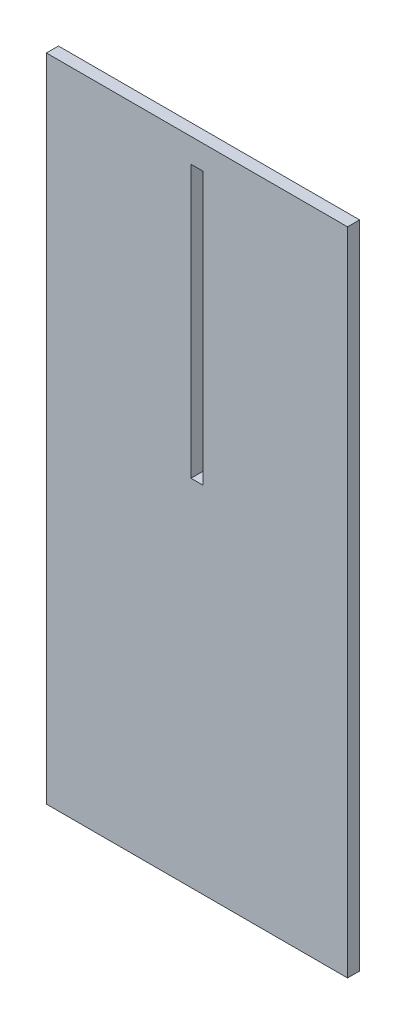
SolidWorks part; units mm, degrees
ref_plane "Front Plane" through (0, 0, 0) normal (0, 0, 1) x (1, 0, 0)
ref_plane "Top Plane" through (0, 0, 0) normal (0, 1, 0) x (1, 0, 0)
ref_plane "Right Plane" through (0, 0, 0) normal (1, 0, 0) x (0, 0, -1)
sketch "Sketch2" plane through (0, 0, 0) normal (0, 0, 1) x (1, 0, 0)
  line L1 (0, 0) -> (125, 0)
  line L2 (0, 0) -> (0, -270)
  line L3 (0, -270) -> (125, -270)
  line L4 (125, 0) -> (125, -270)
  line L5 (60, -10) -> (65, -10)
  line L6 (60, -10) -> (60, -122.8659)
  line L7 (60, -122.8659) -> (65, -122.8659)
  line L8 (65, -10) -> (65, -122.8659)
  dimension "D1" = 270
  dimension "D2" = 125
  dimension "D3" = 5
  dimension "D4" = 10
  dimension "D5" = 60
extrude "Boss-Extrude2" add sketch "Sketch2" along normal blind 5
